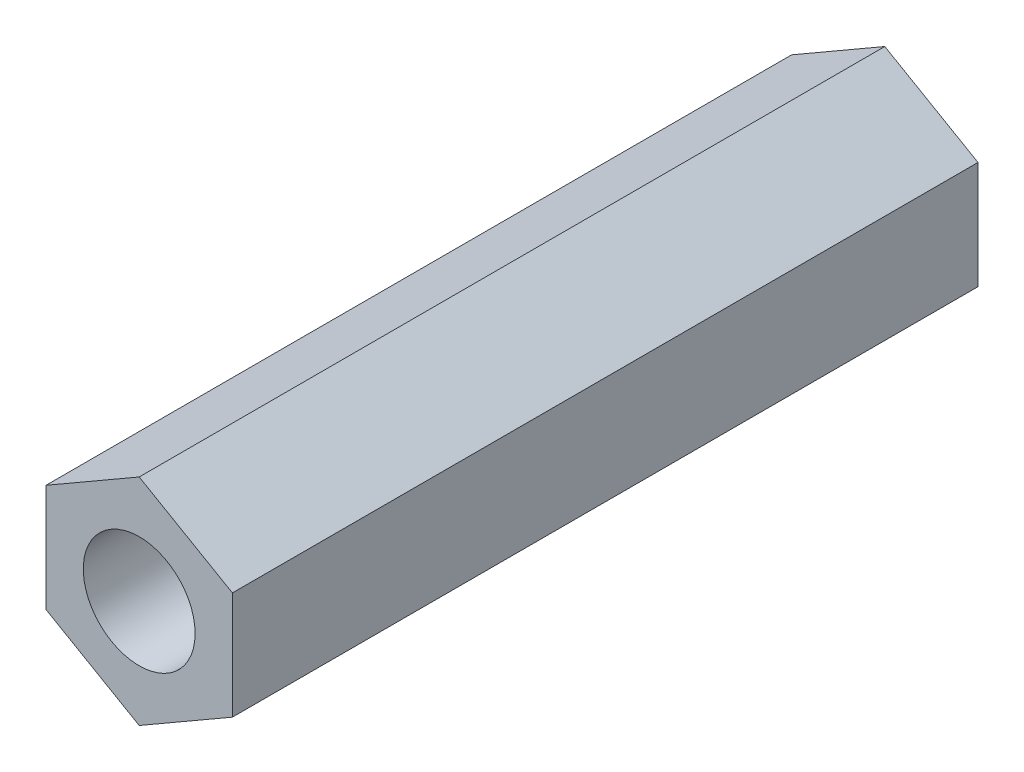
SolidWorks part; units mm, degrees
ref_plane "正面" through (0, 0, 0) normal (0, 0, 1) x (1, 0, 0)
ref_plane "平面" through (0, 0, 0) normal (0, 1, 0) x (1, 0, 0)
ref_plane "右側面" through (0, 0, 0) normal (1, 0, 0) x (0, 0, -1)
sketch "ｽｹｯﾁ1" plane through (0, 0, 0) normal (0, 0, 1) x (1, 0, 0)
  line L1 (0, -2.8868) -> (2.5, -1.4434)
  line L2 (2.5, -1.4434) -> (2.5, 1.4434)
  line L3 (2.5, 1.4434) -> (0, 2.8868)
  line L4 (0, 2.8868) -> (-2.5, 1.4434)
  line L5 (-2.5, 1.4434) -> (-2.5, -1.4434)
  line L6 (-2.5, -1.4434) -> (0, -2.8868)
  circle A0 centre (0, 0) radius 2.5 construction
  circle A1 centre (0, 0) radius 1.5
  dimension "D1" = 5
  dimension "D2" = 3
extrude "ﾎﾞｽ - 押し出し1" add sketch "ｽｹｯﾁ1" along normal blind 20
sketch "ｽｹｯﾁ3" plane through (0, 0, 0) normal (0, 0, 1) x (1, 0, 0)
  circle A0 centre (0, 0) radius 1.5
curve "ﾍﾘｶﾙ ｶｰﾌﾞ/ｽﾊﾟｲﾗﾙ ｶｰﾌﾞ1" pitch 0.5 height 40 turns 80
sketch "ｽｹｯﾁ5" plane through (0, 0, 0) normal (0, 1, 0) x (1, 0, 0)
  line L0 (1.5, 0) -> (1.5, 0.44)
  line L1 (1.5, 0.44) -> (1.77, 0.2841)
  line L2 (1.77, 0.2841) -> (1.77, 0.1559)
  line L3 (1.77, 0.1559) -> (1.5, 0)
  dimension "D1" = 0.44
  dimension "D2" = 60
  dimension "D3" = 60
  dimension "D4" = 0.27
sketch "ｽｹｯﾁ7" plane through (0, 0, 0) normal (0, 0, -1) x (-1, 0, 0)
  circle A0 centre (0, 0) radius 1.5
curve "ﾍﾘｶﾙ ｶｰﾌﾞ/ｽﾊﾟｲﾗﾙ ｶｰﾌﾞ2" pitch 0.5 height 20 turns 40
